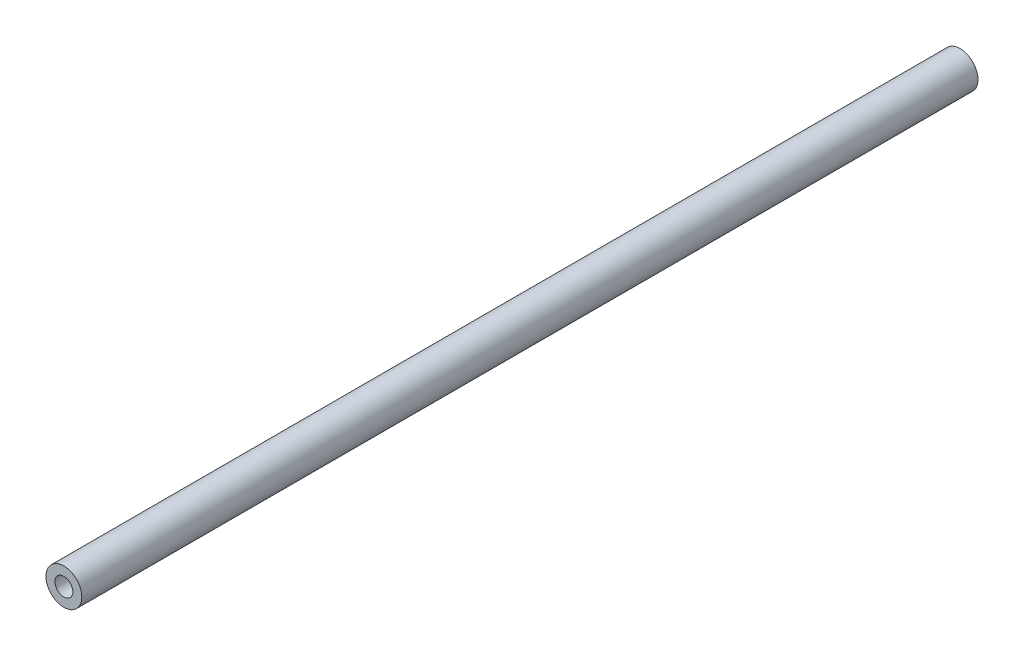
SolidWorks part; units mm, degrees
material "6061-T6 (SS)"
ref_plane "Front" through (0, 0, 0) normal (0, 0, 1) x (1, 0, 0)
ref_plane "Top" through (0, 0, 0) normal (0, 1, 0) x (1, 0, 0)
ref_plane "Right" through (0, 0, 0) normal (1, 0, 0) x (0, 0, -1)
sketch "Sketch1" plane through (0, 0, 0) normal (0, 0, 1) x (1, 0, 0)
  circle A0 centre (0, 0) radius 4
  circle A1 centre (0, 0) radius 2
  dimension "D1" = 8
  dimension "D2" = 4
extrude "Boss-Extrude1" add sketch "Sketch1" along normal mid plane 200
